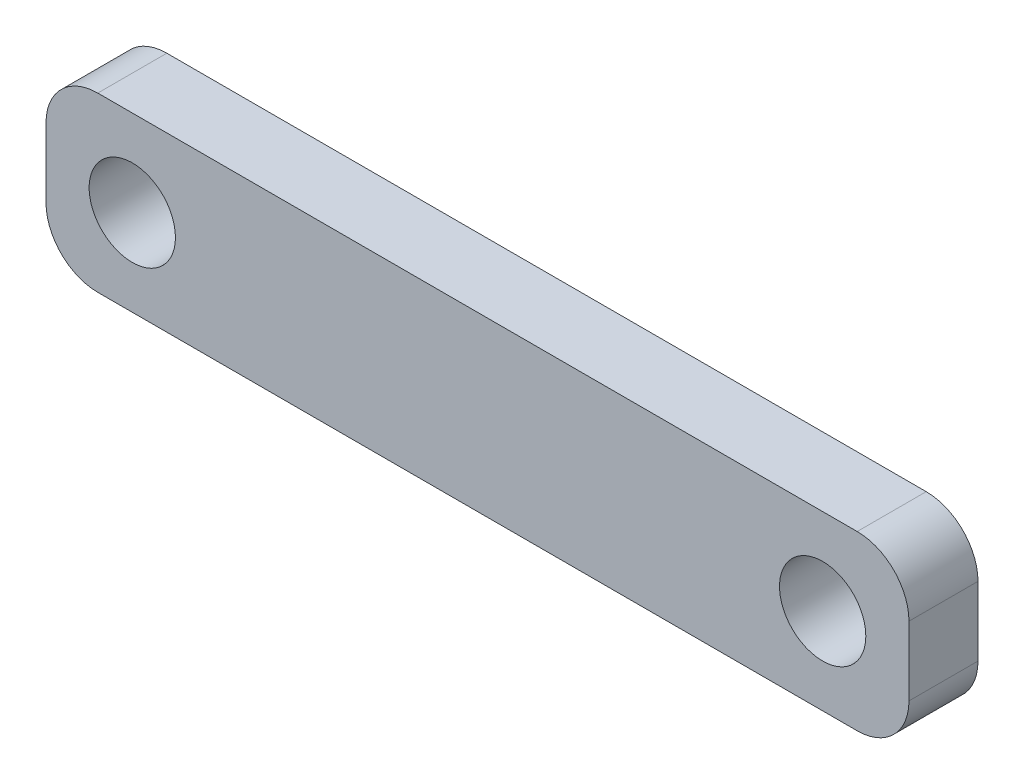
SolidWorks part; units mm, degrees
ref_plane "Front Plane" through (0, 0, 0) normal (0, 0, 1) x (1, 0, 0)
ref_plane "Top Plane" through (0, 0, 0) normal (0, 1, 0) x (1, 0, 0)
ref_plane "Right Plane" through (0, 0, 0) normal (1, 0, 0) x (0, 0, -1)
sketch "Sketch1" plane through (0, 0, 0) normal (0, 0, 1) x (1, 0, 0)
  line L1 (0, 0) -> (-50, 0)
  line L2 (0, 0) -> (0, -10)
  line L3 (0, -10) -> (-50, -10)
  line L4 (-50, 0) -> (-50, -10)
  circle A0 centre (-5, -5) radius 2.5
  circle A1 centre (-45, -5) radius 2.5
  point P9 (0, 0)
  dimension "D3" = 5
  dimension "D7" = 5
  dimension "D1" = 40
  dimension "D2" = 10
  dimension "D4" = 5
  dimension "D5" = 5
  dimension "D6" = 5
extrude "Boss-Extrude1" add sketch "Sketch1" along normal blind 4 contours L1 L4 L3 L2 A1 A0
fillet "Fillet1" radius 3 4 edges at (0, -10, 2) (0, 0, 2) (-50, -10, 2) (-50, 0, 2)
